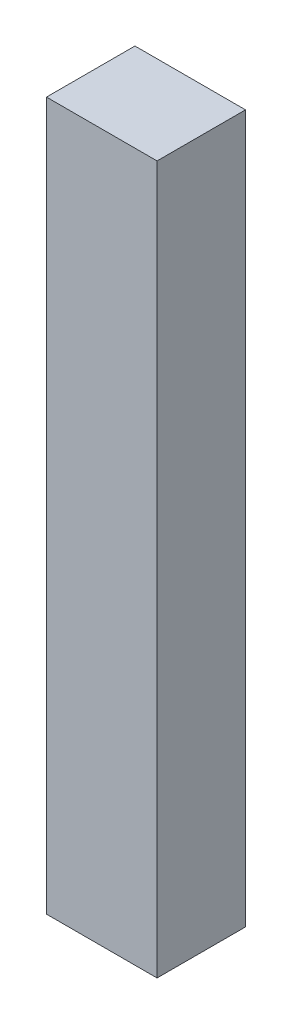
SolidWorks part; units mm, degrees
ref_plane "Front Plane" through (0, 0, 0) normal (0, 0, 1) x (1, 0, 0)
ref_plane "Top Plane" through (0, 0, 0) normal (0, 1, 0) x (1, 0, 0)
ref_plane "Right Plane" through (0, 0, 0) normal (1, 0, 0) x (0, 0, -1)
sketch "Sketch1" plane through (0, 0, 0) normal (0, 0, 1) x (1, 0, 0)
  line L1 (-125, 800) -> (125, 800)
  line L2 (-125, 800) -> (-125, -800)
  line L3 (-125, -800) -> (125, -800)
  line L4 (125, 800) -> (125, -800)
  line L5 (-125, 800) -> (125, -800) construction
  line L6 (-125, -800) -> (125, 800) construction
  point P0 (0, 0)
  dimension "D1" = 250
  dimension "D2" = 1600
extrude "Boss-Extrude1" add sketch "Sketch1" along normal blind 200
